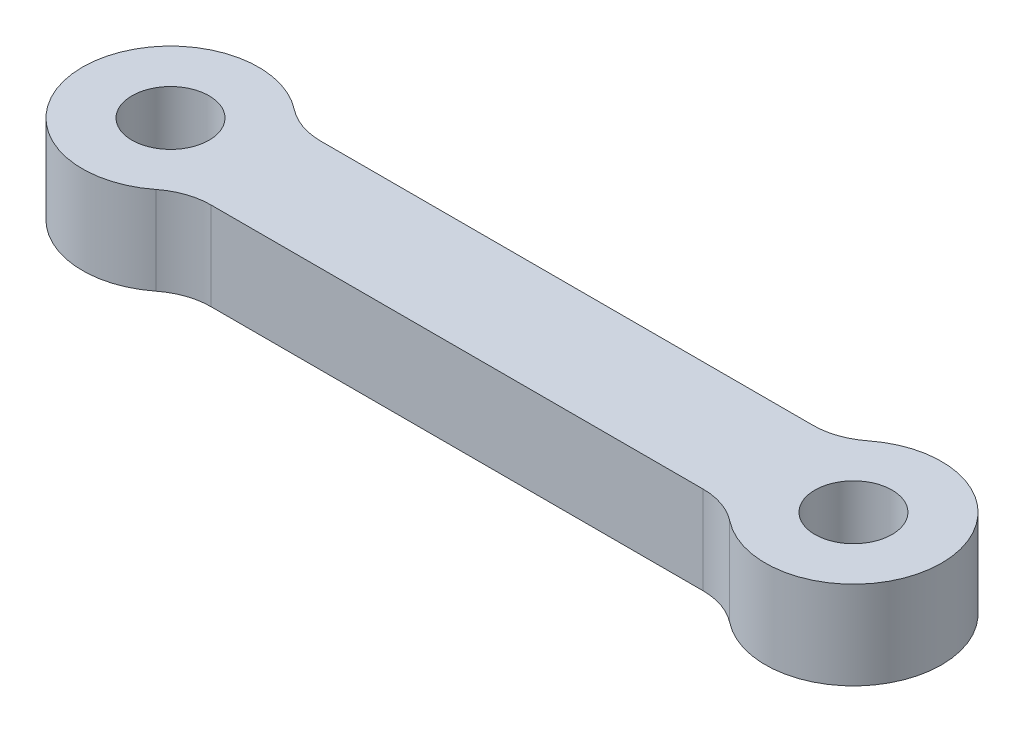
SolidWorks part; units mm, degrees
ref_plane "Front Plane" through (0, 0, 0) normal (0, 0, 1) x (1, 0, 0)
ref_plane "Top Plane" through (0, 0, 0) normal (0, 1, 0) x (1, 0, 0)
ref_plane "Right Plane" through (0, 0, 0) normal (1, 0, 0) x (0, 0, -1)
sketch "Sketch1" plane through (0, 0, 0) normal (0, 1, 0) x (1, 0, 0)
  line L0 (3.1225, 2.5) -> (27.8775, 2.5)
  line L1 (3.1225, -2.5) -> (27.8775, -2.5)
  line L2 (0, 0) -> (31, 0) construction
  circle A0 centre (0, 0) radius 4
  circle A2 centre (0, 0) radius 1.75
  circle A3 centre (31, 0) radius 1.75
  circle A4 centre (31, 0) radius 4
  point P11 (27.4934, 1.9244)
  point P12 (1.7184, 3.6121)
  dimension "D1" = 3.5
  dimension "D3" = 8
  dimension "D2" = 31
  dimension "D4" = 5
extrude "Boss-Extrude1" add sketch "Sketch1" along normal blind 4
fillet "Fillet1" radius 3 4 edges at (27.8775, 2, -2.5) (3.1225, 2, -2.5) (3.1225, 2, 2.5) (27.8775, 2, 2.5)
